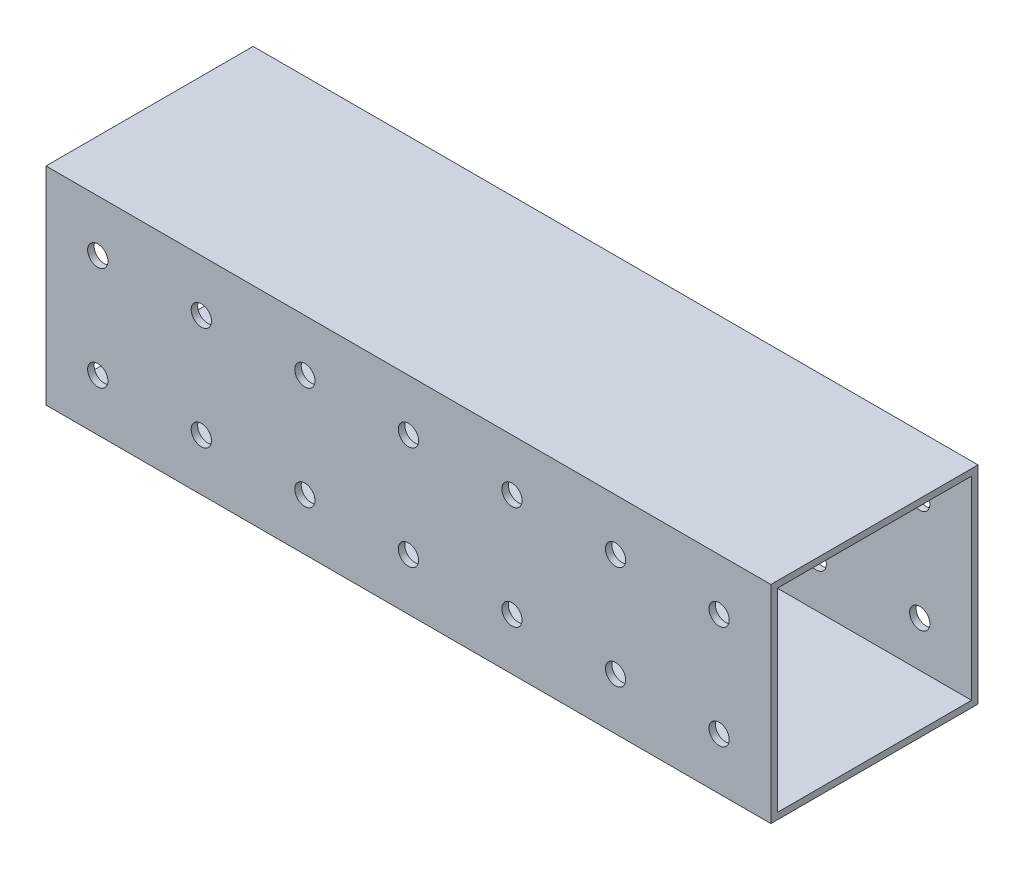
SolidWorks part; units mm, degrees
material "6061-T6 (SS)"
ref_plane "Front Plane" through (0, 0, 0) normal (0, 0, 1) x (1, 0, 0)
ref_plane "Top Plane" through (0, 0, 0) normal (0, 1, 0) x (1, 0, 0)
ref_plane "Right Plane" through (0, 0, 0) normal (1, 0, 0) x (0, 0, -1)
sketch "Sketch1" plane through (0, 0, 0) normal (1, 0, 0) x (0, 0, -1)
  line L1 (0, 0) -> (50.8, 0)
  line L2 (0, 0) -> (0, 50.8)
  line L3 (0, 50.8) -> (50.8, 50.8)
  line L4 (50.8, 0) -> (50.8, 50.8)
  dimension "D1" = 50.8
extrude "Boss-Extrude1" add sketch "Sketch1" along normal blind 177.8
shell "Shell1" thickness 1.5875
sketch "Sketch2" plane through (0, 0, -50.8) normal (0, 0, -1) x (-1, 0, 0)
  line L0 (-177.8, 0) -> (0, 0) construction
  line L1 (0, 0) -> (0, 50.8) construction
  circle A0 centre (-12.7, 12.7) radius 2.4892
  circle A1 centre (-12.7, 38.1) radius 2.4892
  point P8 (0, 0)
  dimension "D1" = 25.4
  dimension "D3" = 12.7
  dimension "D4" = 4.9784
  dimension "D2" = 12.7
extrude "Cut-Extrude1" cut sketch "Sketch2" against normal through all
pattern_linear "LPattern1" count 7 spacing 25.4 along (1, 0, 0) of "Cut-Extrude1"
